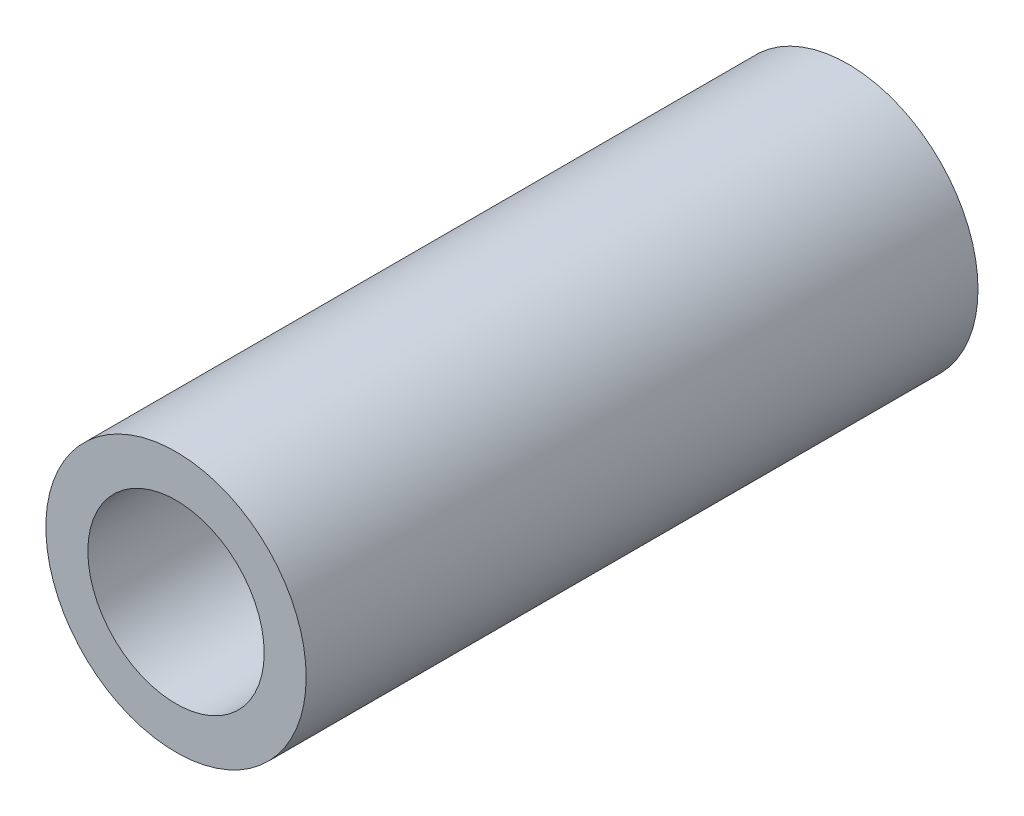
SolidWorks part; units mm, degrees
ref_plane "Front Plane" through (0, 0, 0) normal (0, 0, 1) x (1, 0, 0)
ref_plane "Top Plane" through (0, 0, 0) normal (0, 1, 0) x (1, 0, 0)
ref_plane "Right Plane" through (0, 0, 0) normal (1, 0, 0) x (0, 0, -1)
sketch "Sketch1" plane through (0, 0, 0) normal (0, 0, 1) x (1, 0, 0)
  circle A0 centre (0, 0) radius 2.1
  circle A1 centre (0, 0) radius 3.1
  dimension "D1" = 4.2
  dimension "D2" = 1
extrude "Boss-Extrude1" add sketch "Sketch1" along normal blind 16
